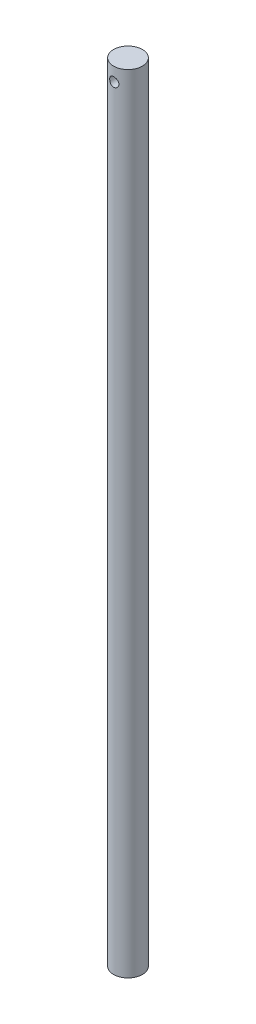
SolidWorks part; units mm, degrees
ref_plane "Frontal Plane" through (0, 0, 0) normal (0, 0, 1) x (1, 0, 0)
ref_plane "Horizontal Plane" through (0, 0, 0) normal (0, 1, 0) x (1, 0, 0)
ref_plane "Profile Plane" through (0, 0, 0) normal (1, 0, 0) x (0, 0, -1)
sketch "Sketch1" plane through (0, 0, 0) normal (0, 1, 0) x (1, 0, 0)
  circle A0 centre (0, 0) radius 9.906
  dimension "D1" = 19.812
extrude "Boss-Extrude1" add sketch "Sketch1" along normal blind 539.75
sketch "Sketch2" plane through (0, 0, 0) normal (0, 0, 1) x (1, 0, 0)
  line L0 (9.906, 539.75) -> (-9.906, 539.75) construction
  circle A0 centre (0, 530.352) radius 3.175
  dimension "D1" = 6.35
  dimension "D2" = 9.398
extrude "Cut-Extrude1" cut sketch "Sketch2" against normal through all both and the other way through all
